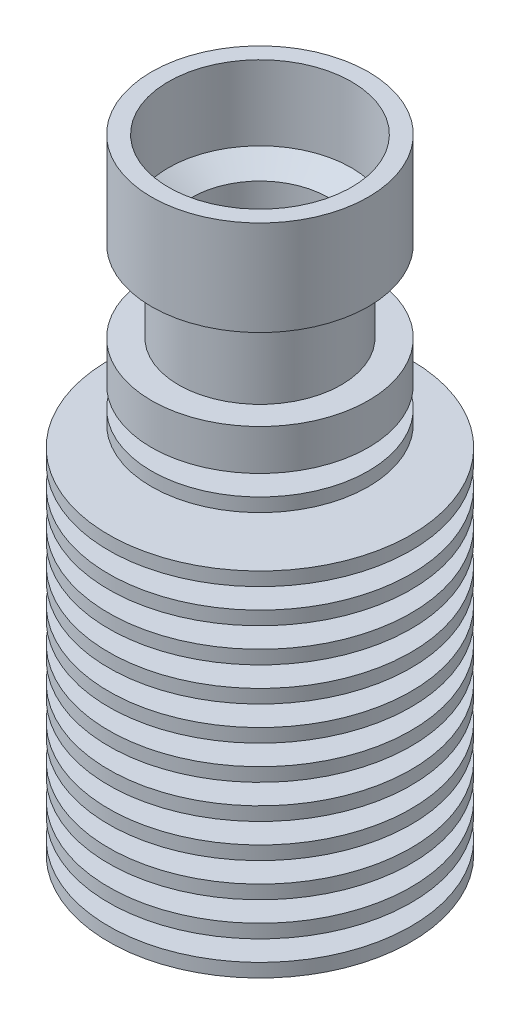
SolidWorks part; units mm, degrees
material "6061 Alloy"
ref_plane "Front Plane" through (0, 0, 0) normal (0, 0, 1) x (1, 0, 0)
ref_plane "Top Plane" through (0, 0, 0) normal (0, 1, 0) x (1, 0, 0)
ref_plane "Right Plane" through (0, 0, 0) normal (1, 0, 0) x (0, 0, -1)
sketch "Sketch1" plane through (0, 0, 0) normal (0, 0, 1) x (1, 0, 0)
  line L0 (0, 0) -> (0, 137.8569) construction
  line L1 (0, 0) -> (11.15, 0)
  line L2 (11.15, 0) -> (11.15, 1)
  line L3 (11.15, 1) -> (5.5, 1)
  line L4 (5.5, 1) -> (5.5, 2.5)
  line L5 (5.5, 2.5) -> (11.15, 2.5)
  line L6 (11.15, 2.5) -> (11.15, 3.5)
  line L7 (11.15, 3.5) -> (5.4, 3.5)
  line L8 (5.4, 3.5) -> (5.4, 5)
  line L9 (5.4, 5) -> (11.15, 5)
  line L10 (11.15, 5) -> (11.15, 6)
  line L11 (11.15, 6) -> (5.3, 6)
  line L12 (5.3, 6) -> (5.3, 7.5)
  line L13 (5.3, 7.5) -> (11.15, 7.5)
  line L14 (11.15, 7.5) -> (11.15, 8.5)
  line L15 (11.15, 8.5) -> (5.2, 8.5)
  line L16 (5.2, 8.5) -> (5.2, 10)
  line L17 (5.2, 10) -> (11.15, 10)
  line L18 (11.15, 10) -> (11.15, 11)
  line L19 (11.15, 11) -> (5.1, 11)
  line L20 (5.1, 11) -> (5.1, 12.5)
  line L21 (5.1, 12.5) -> (11.15, 12.5)
  line L22 (11.15, 12.5) -> (11.15, 13.5)
  line L23 (11.15, 13.5) -> (5, 13.5)
  line L24 (5, 13.5) -> (5, 15)
  line L25 (5, 15) -> (11.15, 15)
  line L26 (11.15, 15) -> (11.15, 16)
  line L27 (11.15, 16) -> (4.9, 16)
  line L28 (4.9, 16) -> (4.9, 17.5)
  line L29 (4.9, 17.5) -> (11.15, 17.5)
  line L30 (11.15, 17.5) -> (11.15, 18.5)
  line L31 (11.15, 18.5) -> (4.8, 18.5)
  line L32 (4.8, 18.5) -> (4.8, 20)
  line L33 (4.8, 20) -> (11.15, 20)
  line L34 (11.15, 20) -> (11.15, 21)
  line L35 (11.15, 21) -> (4.7, 21)
  line L36 (4.7, 21) -> (4.7, 22.5)
  line L37 (4.7, 22.5) -> (11.15, 22.5)
  line L38 (11.15, 22.5) -> (11.15, 23.5)
  line L39 (11.15, 23.5) -> (4.6, 23.5)
  line L40 (4.6, 23.5) -> (4.6, 25)
  line L41 (4.6, 25) -> (11.15, 25)
  line L42 (11.15, 25) -> (11.15, 26)
  line L43 (11.15, 26) -> (4.5, 26)
  line L44 (4.5, 26) -> (4.5, 27.5)
  line L45 (4.5, 27.5) -> (8, 27.5)
  line L46 (8, 27.5) -> (8, 28.5)
  line L47 (8, 28.5) -> (4.4, 28.5)
  line L48 (4.4, 28.5) -> (4.4, 30)
  line L49 (4.4, 30) -> (8, 30)
  line L50 (8, 30) -> (8, 33)
  line L51 (8, 33) -> (6, 33)
  line L52 (6, 33) -> (6, 39)
  line L53 (6, 39) -> (8, 39)
  line L54 (8, 39) -> (8, 46)
  line L55 (8, 46) -> (0, 46)
  line L56 (0, 46) -> (0, 0)
  line L57 (4.4, 28.5) -> (5.5, 1) construction
  dimension "D1" = 46
  dimension "D2" = 1
  dimension "D3" = 2.5
  dimension "D4" = 22.3
  dimension "D5" = 16
  dimension "D6" = 12
  dimension "D7" = 7
  dimension "D8" = 6
  dimension "D9" = 3
  dimension "D10" = 8.8
  dimension "D11" = 11
revolve "Revolve1" add sketch "Sketch1" angle 360 about L0
sketch "Sketch2" plane through (0, 0, 0) normal (0, 0, 1) x (1, 0, 0)
  line L0 (0, 0) -> (0, 55.4229) construction
  line L1 (0, 46) -> (6.75, 46)
  line L2 (8, 46) -> (-8, 46) construction
  line L3 (6.75, 46) -> (6.75, 40.5)
  line L4 (6.75, 40.5) -> (5, 39.4896)
  line L5 (5, 39.4896) -> (5, 36.4896)
  line L6 (5, 36.4896) -> (3.25, 35.4793)
  line L7 (3.25, 35.4793) -> (3.25, 31.5)
  line L8 (3.25, 31.5) -> (1.6, 30.5474)
  line L9 (1.6, 30.5474) -> (1.6, 18.5196)
  line L10 (1.6, 18.5196) -> (2.5, 18)
  line L11 (2.5, 18) -> (2.5, 14)
  line L12 (2.5, 14) -> (3, 14)
  line L13 (3, 14) -> (3, 0)
  line L14 (-11.15, 0) -> (11.15, 0) construction
  line L15 (3, 0) -> (0, 0)
  line L16 (0, 0) -> (0, 46)
  dimension "D1" = 6.5
  dimension "D2" = 10
  dimension "D3" = 13.5
  dimension "D4" = 120
  dimension "D5" = 120
  dimension "D6" = 3.2
  dimension "D7" = 14.5
  dimension "D8" = 5.5
  dimension "D9" = 3
  dimension "D10" = 18
  dimension "D11" = 14
  dimension "D12" = 6
  dimension "D13" = 5
revolve "Cut-Revolve1" cut sketch "Sketch2" angle 360 about L0
equation "\"D5@Sketch2\"=\"D4@Sketch2\""
